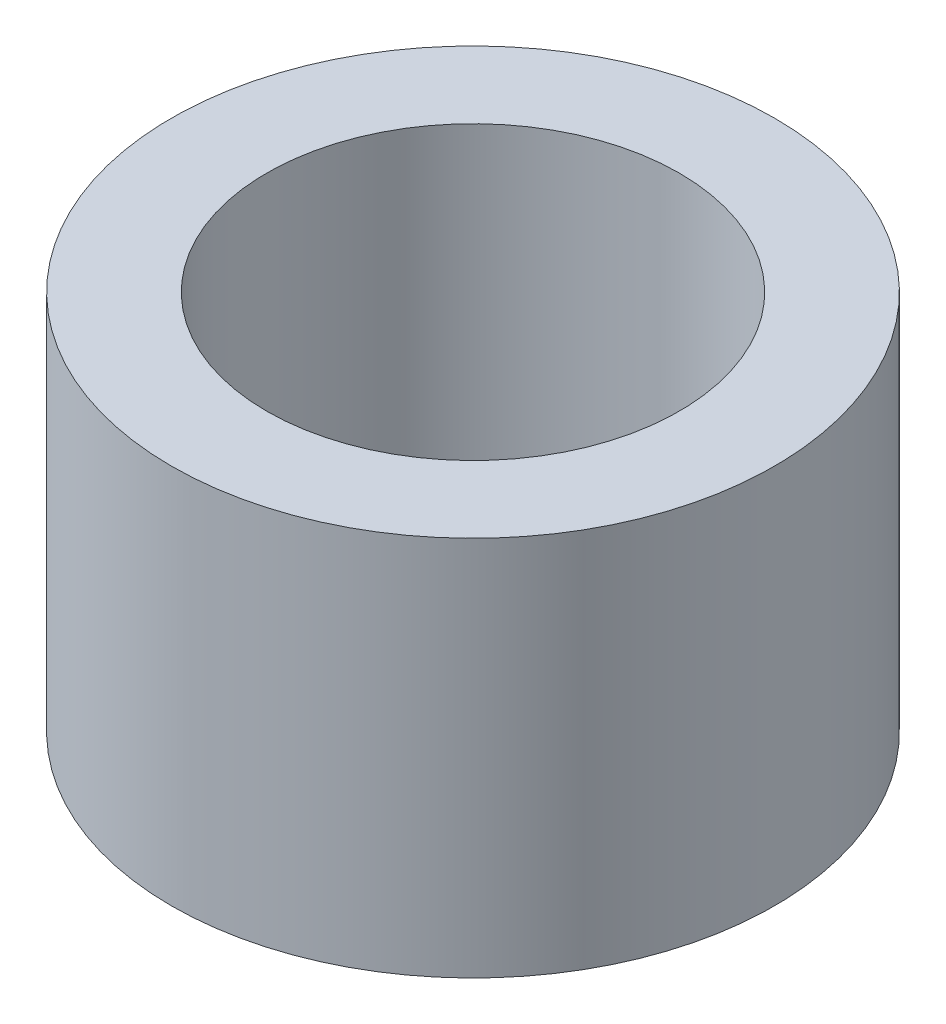
SolidWorks part; units mm, degrees
ref_plane "Front Plane" through (0, 0, 0) normal (0, 0, 1) x (1, 0, 0)
ref_plane "Top Plane" through (0, 0, 0) normal (0, 1, 0) x (1, 0, 0)
ref_plane "Right Plane" through (0, 0, 0) normal (1, 0, 0) x (0, 0, -1)
sketch "Sketch1" plane through (0, 0, 0) normal (0, 1, 0) x (1, 0, 0)
  circle A0 centre (0, 0) radius 4.75
  circle A1 centre (0, 0) radius 3.25
  dimension "D1" = 6.5
  dimension "D2" = 9.5
extrude "Boss-Extrude1" add sketch "Sketch1" along normal blind 6
